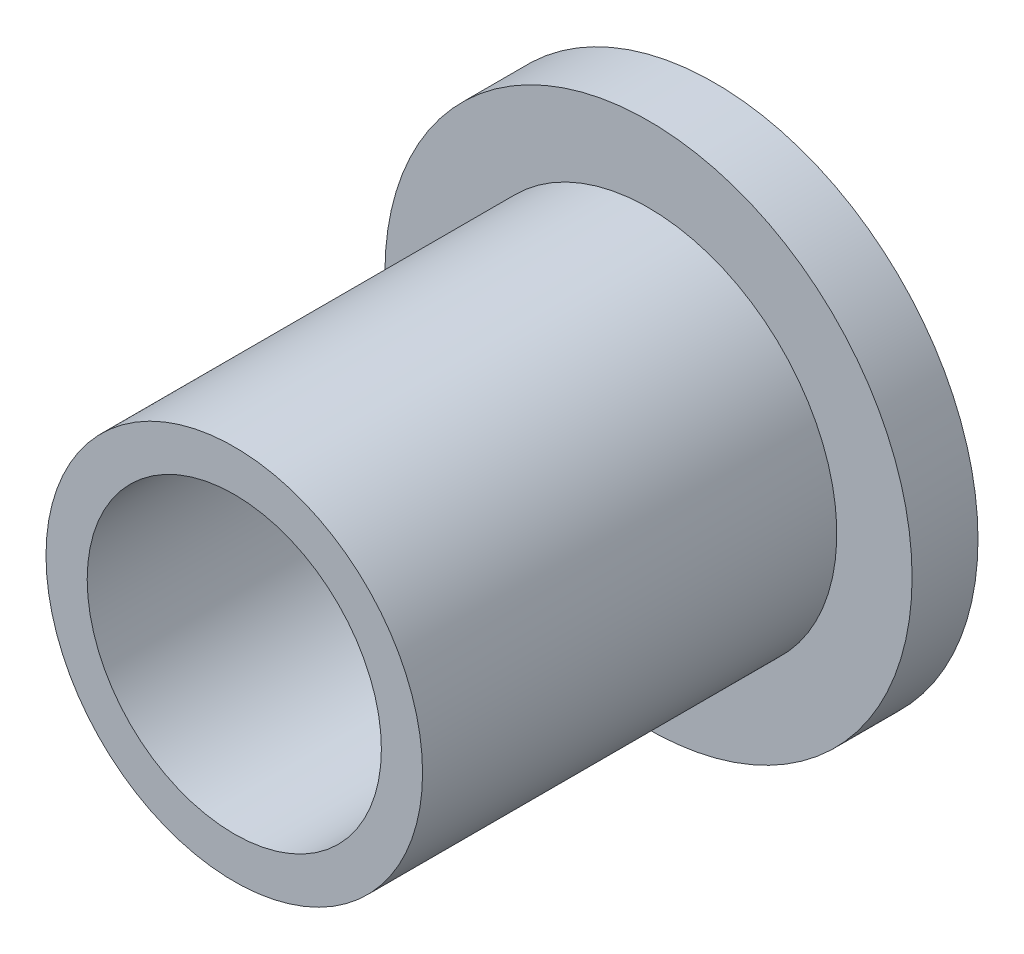
SolidWorks part; units mm, degrees
ref_plane "Front Plane" through (0, 0, 0) normal (0, 0, 1) x (1, 0, 0)
ref_plane "Top Plane" through (0, 0, 0) normal (0, 1, 0) x (1, 0, 0)
ref_plane "Right Plane" through (0, 0, 0) normal (1, 0, 0) x (0, 0, -1)
sketch "Sketch1" plane through (0, 0, 0) normal (0, 0, 1) x (1, 0, 0)
  circle A0 centre (0, 0) radius 3.9688
  circle A1 centre (0, 0) radius 5.08
  dimension "D1" = 7.9375
  dimension "D2" = 10.16
extrude "Extrude1" add sketch "Sketch1" along normal blind 11.176
sketch "Sketch2" plane through (0, 0, 0) normal (0, 0, -1) x (-1, 0, 0)
  circle A0 centre (0, 0) radius 4.0005
  circle A1 centre (0, 0) radius 7.112
extrude "Extrude2" add sketch "Sketch2" along normal blind 1.778
